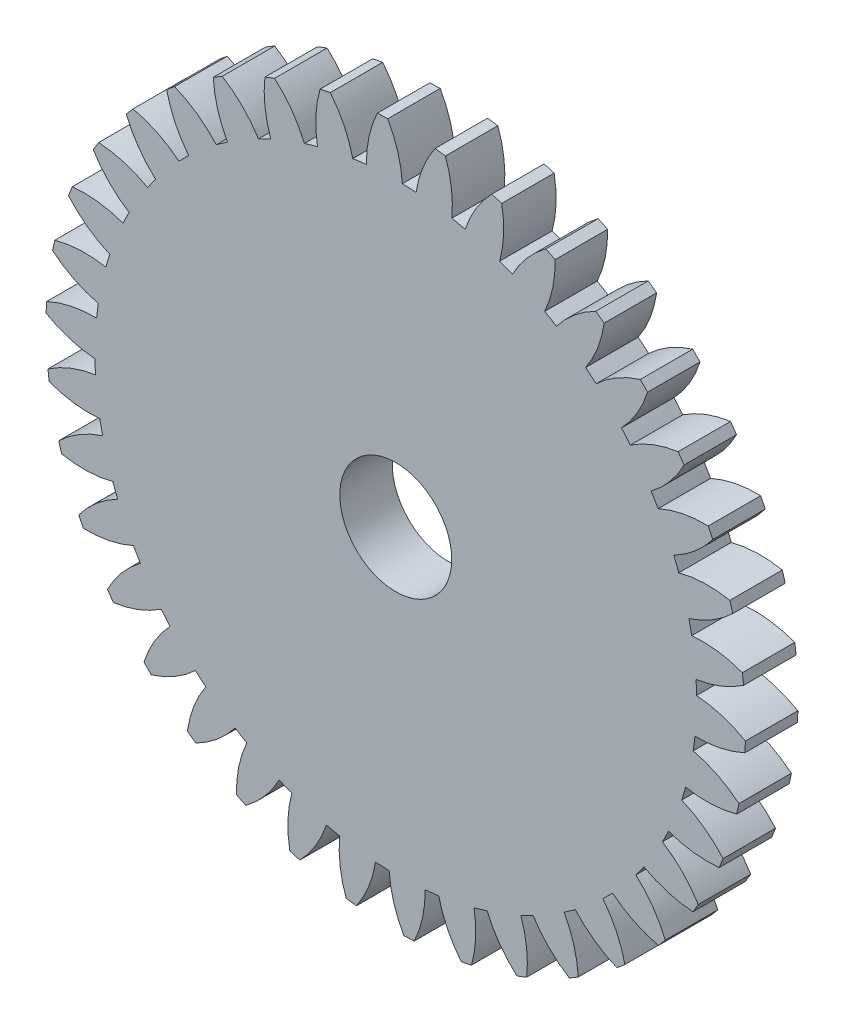
SolidWorks part; units mm, degrees
ref_plane "Alzado" through (0, 0, 0) normal (0, 0, 1) x (1, 0, 0)
ref_plane "Planta" through (0, 0, 0) normal (0, 1, 0) x (1, 0, 0)
ref_plane "Vista lateral" through (0, 0, 0) normal (1, 0, 0) x (0, 0, -1)
sketch "Croquis1" plane through (0, 0, 0) normal (0, 0, 1) x (1, 0, 0)
  line L0 (0, 0) -> (0, 11.1653) construction
  line L1 (0, 0) -> (-3.8952, 10.7019) construction
  line L2 (0, 9.5) -> (-3.0532, 8.3887) construction
  line L3 (0, 0) -> (0.5, 11.1653) construction
  circle A4 centre (0, 0) radius 10
  circle A5 centre (0, 0) radius 8.6
  circle A6 centre (0, 0) radius 9.5
  circle A7 centre (-3.0532, 8.3887) radius 3.2492
  circle A8 centre (3.7908, 8.0822) radius 3.2492
  dimension "D1" = 20
  dimension "D2" = 17.2
  dimension "D3" = 19
  dimension "D4" = 20
  dimension "D5" = 0.5
sketch "Croquis2" plane through (0, 0, 0) normal (0, 0, 1) x (1, 0, 0)
  circle A0 centre (0, 0) radius 10
  circle A1 centre (0, 0) radius 1.6
  dimension "D1" = 3.2
  dimension "D2" = 20
extrude "Saliente-Extruir1" add sketch "Croquis2" along normal blind 1.5
extrude "Cortar-Extruir1" cut sketch "Croquis1" along normal blind 1.5
pattern_circular "MatrizC1" count 38 over 360 about axis through (0, 0, 0) along (0, 0, 1) of "Cortar-Extruir1"
